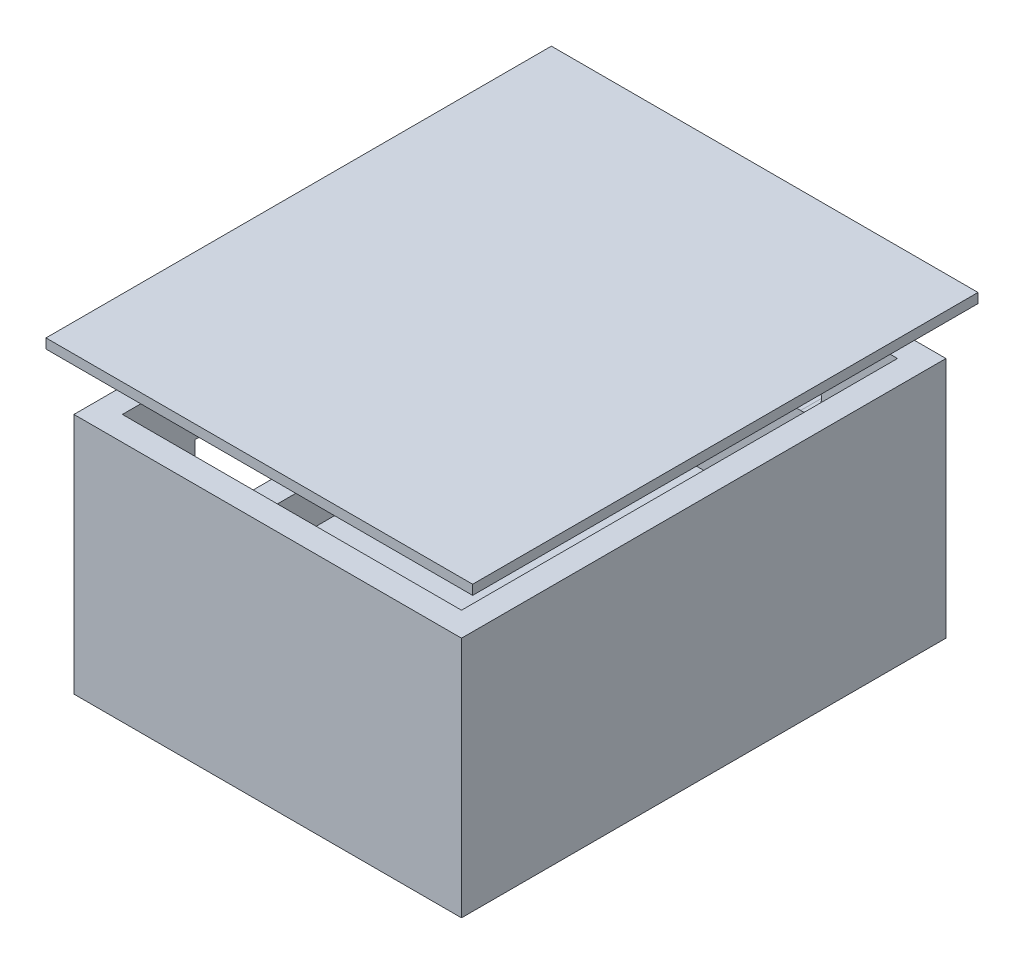
SolidWorks part; units mm, degrees
ref_plane "Front Plane" through (0, 0, 0) normal (0, 0, 1) x (1, 0, 0)
ref_plane "Top Plane" through (0, 0, 0) normal (0, 1, 0) x (1, 0, 0)
ref_plane "Right Plane" through (0, 0, 0) normal (1, 0, 0) x (0, 0, -1)
sketch "Sketch1" plane through (0, 0, 0) normal (0, 1, 0) x (1, 0, 0)
  line L1 (0, 0) -> (101.6, 0)
  line L2 (0, 0) -> (0, 127)
  line L3 (0, 127) -> (101.6, 127)
  line L4 (101.6, 0) -> (101.6, 127)
extrude "Boss-Extrude1" add sketch "Sketch1" along normal blind 63.5
sketch "Sketch2" plane through (0, 63.5, 0) normal (0, 1, 0) x (1, 0, 0)
  line L8 (6.35, 120.65) -> (6.35, 6.35)
  line L9 (6.35, 6.35) -> (95.25, 6.35)
  line L10 (95.25, 6.35) -> (95.25, 120.65)
  line L11 (95.25, 120.65) -> (6.35, 120.65)
  line L12 (6.35, 120.65) -> (6.35, 6.35)
  line L13 (6.35, 6.35) -> (95.25, 6.35)
  line L14 (95.25, 6.35) -> (95.25, 120.65)
  line L15 (95.25, 120.65) -> (6.35, 120.65)
  dimension "D1" = 6.35
extrude "Cut-Extrude1" cut sketch "Sketch2" against normal blind 50.8
sketch "Sketch3" plane through (0, 0, 0) normal (-1, 0, 0) x (0, 0, 1)
  line L2 (-101.6, 48.26) -> (-25.4, 48.26)
  line L4 (-101.6, 48.26) -> (-101.6, 22.86)
  line L6 (-25.4, 48.26) -> (-25.4, 22.86)
  line L7 (-25.4, 22.86) -> (-101.6, 22.86)
extrude "Cut-Extrude2" cut sketch "Sketch3" against normal blind 50.8
ref_plane "Plane1" through (0, 78.74, 0) normal (0, 1, 0) x (1, 0, 0)
sketch "Sketch4" plane through (0, 78.74, 0) normal (0, 1, 0) x (1, 0, 0)
  line L1 (106.0473, 130.9539) -> (-5.7971, 130.9539)
  line L2 (106.0473, 130.9539) -> (106.0473, -1.5286)
  line L3 (106.0473, -1.5286) -> (-5.7971, -1.5286)
  line L4 (-5.7971, 130.9539) -> (-5.7971, -1.5286)
extrude "Boss-Extrude2" add sketch "Sketch4" against normal blind 2.54 separate body
sketch "Sketch5" plane through (0, 76.2, 0) normal (0, -1, 0) x (1, 0, 0)
  line L12 (99.1893, -124.0959) -> (99.1893, -5.3294)
  line L13 (99.1893, -5.3294) -> (1.0609, -5.3294)
  line L14 (1.0609, -5.3294) -> (1.0609, -124.0959)
  line L15 (1.0609, -124.0959) -> (99.1893, -124.0959)
  line L16 (99.1893, -124.0959) -> (99.1893, -5.3294)
  line L17 (99.1893, -5.3294) -> (1.0609, -5.3294)
  line L18 (1.0609, -5.3294) -> (1.0609, -124.0959)
  line L19 (1.0609, -124.0959) -> (99.1893, -124.0959)
  dimension "D1" = 6.858
extrude "Boss-Extrude3" add sketch "Sketch5" along normal blind 2.54
sketch "Sketch7" plane through (0, 0, -127) normal (0, 0, -1) x (-1, 0, 0)
  line L6 (-31.75, 44.45) -> (-69.85, 44.45) construction
  line L8 (-31.75, 39.003) -> (-69.85, 39.003)
  line L9 (-31.75, 49.897) -> (-69.85, 49.897)
  arc A0 (-31.75, 39.003) -> (-31.75, 49.897) centre (-31.75, 44.45) ccw
  arc A1 (-69.85, 49.897) -> (-69.85, 39.003) centre (-69.85, 44.45) ccw
  point P16 (-50.8, 44.45)
extrude "Cut-Extrude3" cut sketch "Sketch7" against normal blind 7.62
